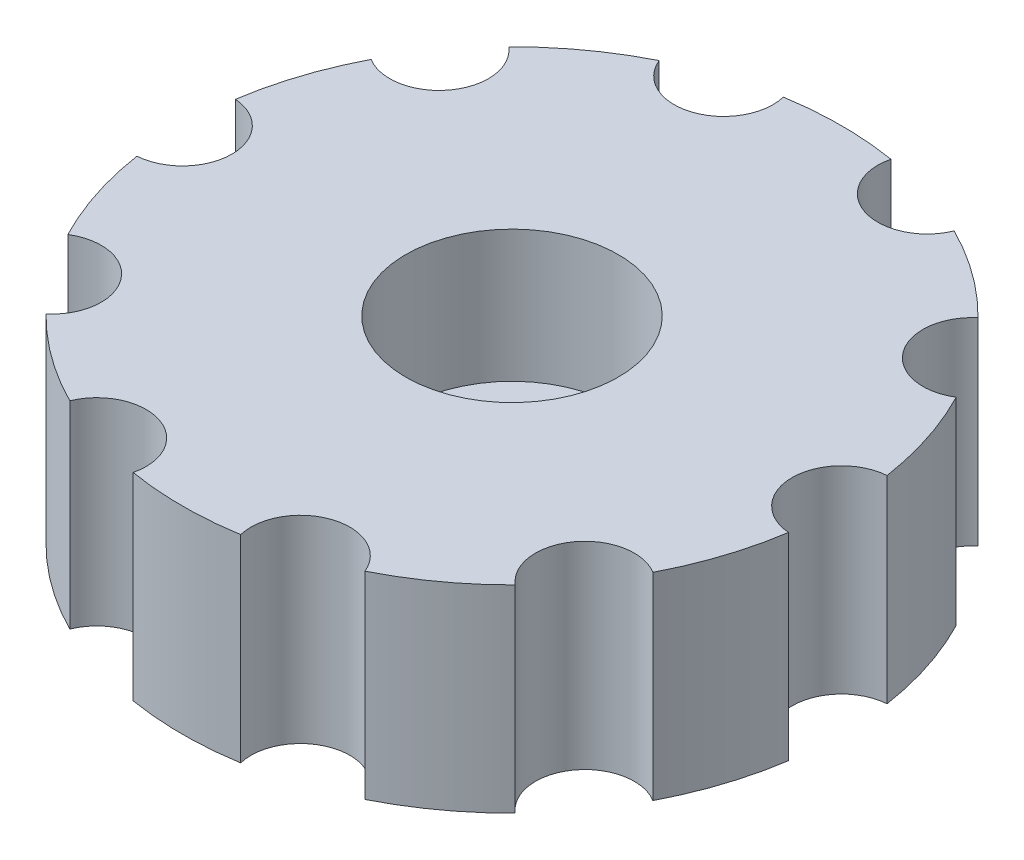
SolidWorks part; units mm, degrees
ref_plane "Front Plane" through (0, 0, 0) normal (0, 0, 1) x (1, 0, 0)
ref_plane "Top Plane" through (0, 0, 0) normal (0, 1, 0) x (1, 0, 0)
ref_plane "Right Plane" through (0, 0, 0) normal (1, 0, 0) x (0, 0, -1)
sketch "Sketch1" plane through (0, 0, 0) normal (0, 1, 0) x (1, 0, 0)
  circle A0 centre (0, 0) radius 20
  circle A1 centre (0, 0) radius 3.25
  dimension "D1" = 40
  dimension "D2" = 6.5
extrude "Boss-Extrude1" add sketch "Sketch1" along normal blind 12
sketch "Sketch2" plane through (0, 12, 0) normal (0, 1, 0) x (1, 0, 0)
  circle A0 centre (0, 0) radius 6.45
  dimension "D1" = 12.9
extrude "Cut-Extrude1" cut sketch "Sketch2" against normal blind 8
sketch "Sketch3" plane through (0, 12, 0) normal (0, 1, 0) x (1, 0, 0)
  circle A0 centre (20, 0) radius 3
  circle A1 centre (0, 0) radius 20 construction
  point P4 (0, 0)
  dimension "D1" = 6
extrude "Cut-Extrude2" cut sketch "Sketch3" against normal through all
pattern_circular "CirPattern1" count 10 over 360 about axis through (0, 0, 0) along (0, 1, 0) of "Cut-Extrude2"
